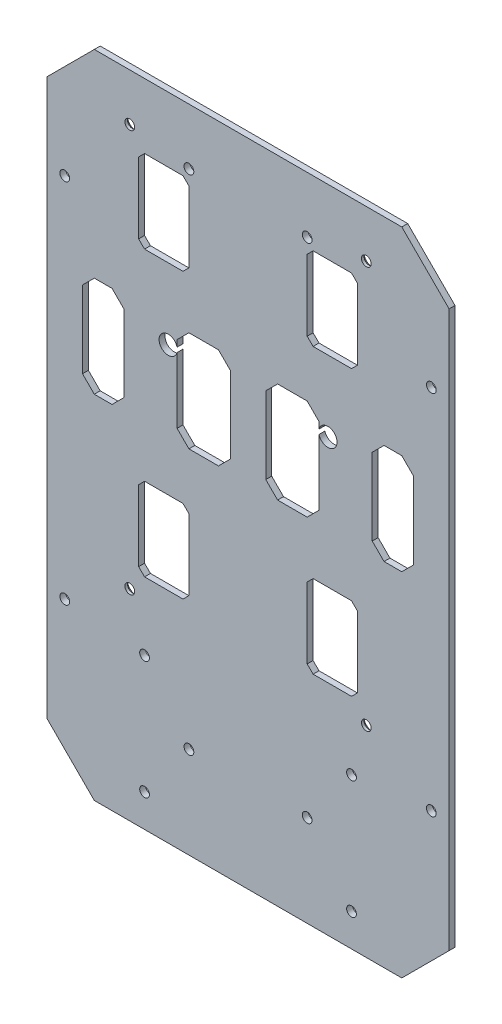
SolidWorks part; units mm, degrees
material "碳纤维板_1600kg_m3"
ref_plane "前视基准面" through (0, 0, 0) normal (0, 0, 1) x (1, 0, 0)
ref_plane "上视基准面" through (0, 0, 0) normal (0, 1, 0) x (1, 0, 0)
ref_plane "右视基准面" through (0, 0, 0) normal (1, 0, 0) x (0, 0, -1)
other "Configuration Table"
sketch "草图6" plane through (0, 0, 0) normal (0, 0, 1) x (1, 0, 0)
  line L144 (-52, -116) -> (52, -116)
  line L145 (52, -116) -> (68, -100)
  line L146 (68, -100) -> (68, 88)
  line L147 (68, 88) -> (52, 104)
  line L148 (52, 104) -> (-52, 104)
  line L149 (-52, 104) -> (-68, 88)
  line L150 (-68, 88) -> (-68, -100)
  line L151 (-68, -100) -> (-52, -116)
  line L152 (-35, -42) -> (-22, -42)
  line L153 (-22, -42) -> (-20, -40)
  line L154 (-20, -40) -> (-20, -16)
  line L155 (-20, -16) -> (-22, -14)
  line L156 (-22, -14) -> (-35, -14)
  line L157 (-35, -14) -> (-37, -16)
  line L158 (-37, -16) -> (-37, -40)
  line L159 (-37, -40) -> (-35, -42)
  line L160 (-35, 54) -> (-22, 54)
  line L161 (-22, 54) -> (-20, 56)
  line L162 (-20, 56) -> (-20, 80)
  line L163 (-20, 80) -> (-22, 82)
  line L164 (-22, 82) -> (-35, 82)
  line L165 (-35, 82) -> (-37, 80)
  line L166 (-37, 80) -> (-37, 56)
  line L167 (-37, 56) -> (-35, 54)
  line L168 (22, -42) -> (35, -42)
  line L169 (35, -42) -> (37, -40)
  line L170 (37, -40) -> (37, -16)
  line L171 (37, -16) -> (35, -14)
  line L172 (35, -14) -> (22, -14)
  line L173 (22, -14) -> (20, -16)
  line L174 (20, -16) -> (20, -40)
  line L175 (20, -40) -> (22, -42)
  line L176 (22, 54) -> (35, 54)
  line L177 (35, 54) -> (37, 56)
  line L178 (37, 56) -> (37, 80)
  line L179 (37, 80) -> (35, 82)
  line L180 (35, 82) -> (22, 82)
  line L181 (22, 82) -> (20, 80)
  line L182 (20, 80) -> (20, 56)
  line L183 (20, 56) -> (22, 54)
  line L184 (-20, 3) -> (-10, 3)
  line L185 (-10, 3) -> (-6, 7)
  line L186 (-6, 7) -> (-6, 33)
  line L187 (-6, 33) -> (-10, 37)
  line L188 (-10, 37) -> (-20, 37)
  line L189 (-20, 37) -> (-24, 33)
  line L190 (-24, 33) -> (-24, 7)
  line L191 (-24, 7) -> (-20, 3)
  line L192 (-52, 3) -> (-46, 3)
  line L193 (-46, 3) -> (-42, 7)
  line L194 (-42, 7) -> (-42, 33)
  line L195 (-42, 33) -> (-46, 37)
  line L196 (-46, 37) -> (-52, 37)
  line L197 (-52, 37) -> (-56, 33)
  line L198 (-56, 33) -> (-56, 7)
  line L199 (-56, 7) -> (-52, 3)
  line L200 (10, 3) -> (20, 3)
  line L201 (20, 3) -> (24, 7)
  line L202 (24, 7) -> (24, 33)
  line L203 (24, 33) -> (20, 37)
  line L204 (20, 37) -> (10, 37)
  line L205 (10, 37) -> (6, 33)
  line L206 (6, 33) -> (6, 7)
  line L207 (6, 7) -> (10, 3)
  line L208 (46, 3) -> (52, 3)
  line L209 (52, 3) -> (56, 7)
  line L210 (56, 7) -> (56, 33)
  line L211 (56, 33) -> (52, 37)
  line L212 (52, 37) -> (46, 37)
  line L213 (46, 37) -> (42, 33)
  line L214 (42, 33) -> (42, 7)
  line L215 (42, 7) -> (46, 3)
  circle A32 centre (-20, -85) radius 1.65
  circle A33 centre (-62, -62) radius 1.65
  circle A34 centre (-40, -48) radius 1.65
  circle A35 centre (-35, -105) radius 1.65
  circle A36 centre (-20, 85) radius 1.65
  circle A37 centre (-62, 62) radius 1.65
  circle A38 centre (-40, 88) radius 1.65
  circle A39 centre (-35, -65) radius 1.65
  circle A40 centre (20, -85) radius 1.65
  circle A41 centre (62, -62) radius 1.65
  circle A42 centre (40, -48) radius 1.65
  circle A43 centre (35, -105) radius 1.65
  circle A44 centre (20, 85) radius 1.65
  circle A45 centre (62, 62) radius 1.65
  circle A46 centre (40, 88) radius 1.65
  circle A47 centre (35, -65) radius 1.65
extrude "紧凑甲板_前后柱位_绑带槽" add sketch "草图6" along normal blind 2
sketch "草图7" plane through (0, 0, 0) normal (0, 0, 1) x (1, 0, 0)
  circle A0 centre (-27, -30) radius 3.1
  circle A1 centre (-27, 30) radius 3.1
  circle A2 centre (27, -30) radius 3.1
  circle A3 centre (27, 30) radius 3.1
extrude "飞控上端螺钉头避让" cut sketch "草图7" along normal blind 2
sketch "草图8" plane through (0, 0, 0) normal (0, 0, 1) x (1, 0, 0)
  circle A0 centre (-40, -48) radius 2.75
  circle A1 centre (-40, 88) radius 2.75
  circle A2 centre (40, -48) radius 2.75
  circle A3 centre (40, 88) radius 2.75
extrude "侧鞍下沉头孔_D5p5深1p1" cut sketch "草图8" along normal blind 1.1 draft 45
